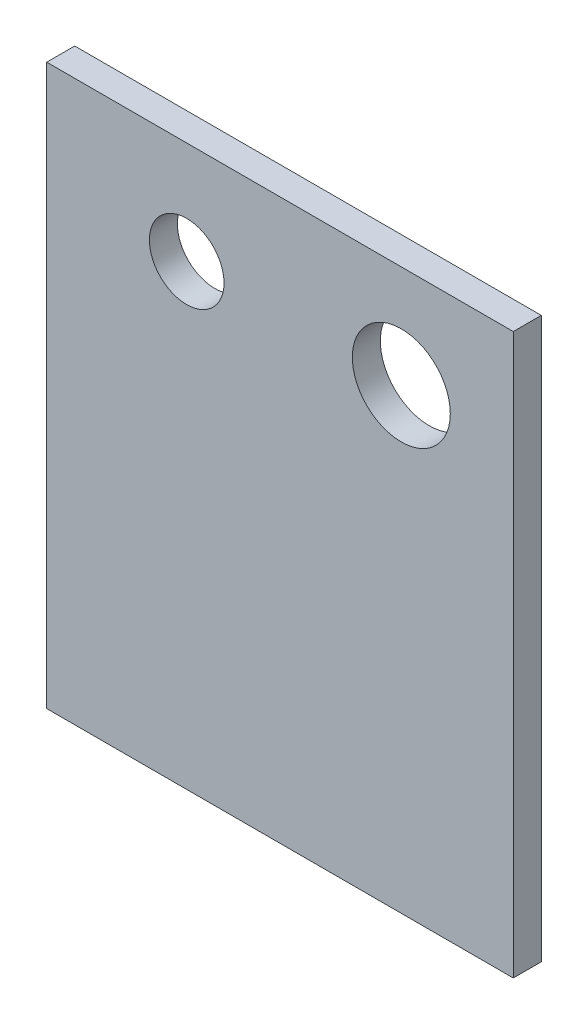
SolidWorks part; units mm, degrees
ref_plane "Front Plane" through (0, 0, 0) normal (0, 0, 1) x (1, 0, 0)
ref_plane "Top Plane" through (0, 0, 0) normal (0, 1, 0) x (1, 0, 0)
ref_plane "Right Plane" through (0, 0, 0) normal (1, 0, 0) x (0, 0, -1)
sketch "Sketch1" plane through (0, 0, 0) normal (0, 0, 1) x (1, 0, 0)
  line L1 (-25, -30) -> (25, -30)
  line L2 (-25, -30) -> (-25, 30)
  line L3 (-25, 30) -> (25, 30)
  line L4 (25, -30) -> (25, 30)
  line L5 (-25, -30) -> (25, 30) construction
  line L6 (-25, 30) -> (25, -30) construction
  circle A0 centre (-10, 19) radius 4
  point P0 (0, 0)
  dimension "D3" = 11
  dimension "D1" = 60
  dimension "D2" = 50
  dimension "D4" = 15
extrude "Boss-Extrude1" add sketch "Sketch1" along normal blind 3
sketch "Sketch2" plane through (0, 0, 0) normal (0, 0, 1) x (1, 0, 0)
  line L0 (25, 30) -> (-25, 30) construction
  line L1 (-25, 30) -> (-25, -30) construction
  circle A0 centre (13, 19) radius 5.25
  dimension "D1" = 10.5
  dimension "D2" = 11
  dimension "D3" = 38
extrude "Cut-Extrude2" cut sketch "Sketch2" along normal through all
